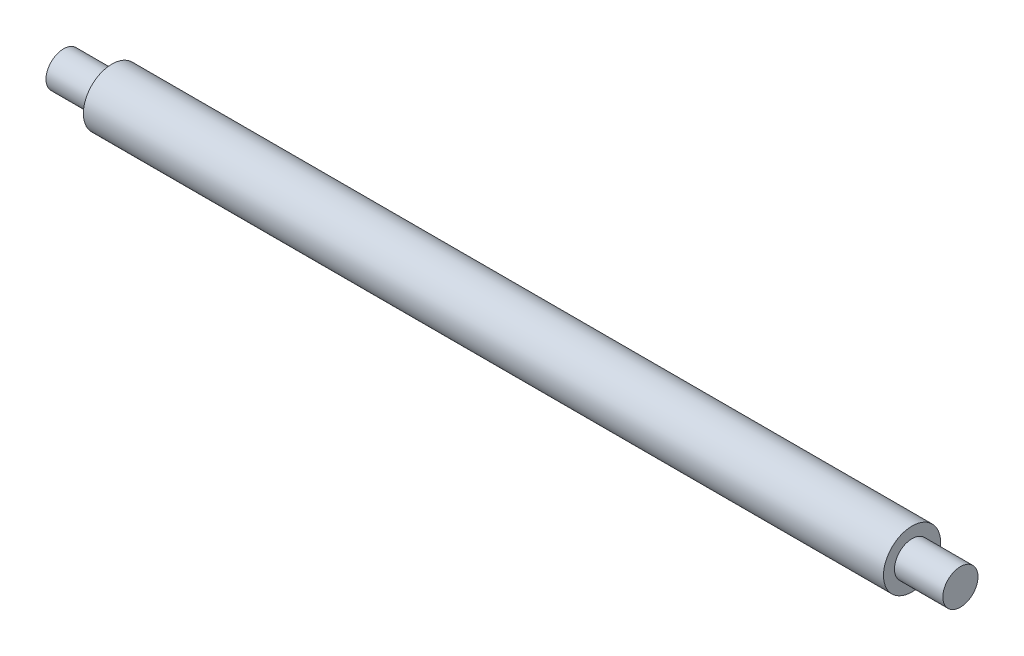
SolidWorks part; units mm, degrees
ref_plane "Front Plane" through (0, 0, 0) normal (0, 0, 1) x (1, 0, 0)
ref_plane "Top Plane" through (0, 0, 0) normal (0, 1, 0) x (1, 0, 0)
ref_plane "Right Plane" through (0, 0, 0) normal (1, 0, 0) x (0, 0, -1)
sketch "Sketch1" plane through (0, 0, 0) normal (0, 0, 1) x (1, 0, 0)
  line L0 (0, 0) -> (204, 0)
  line L1 (204, 0) -> (204, 4)
  line L2 (204, 4) -> (193, 4)
  line L3 (193, 4) -> (193, 6.5)
  line L4 (193, 6.5) -> (11, 6.5)
  line L5 (11, 6.5) -> (11, 4)
  line L6 (11, 4) -> (0, 4)
  line L7 (0, 4) -> (0, 0)
  dimension "D1" = 4
  dimension "D2" = 11
  dimension "D3" = 182
  dimension "D4" = 11
  dimension "D5" = 4
  dimension "D6" = 6.5
revolve "Revolve1" add sketch "Sketch1" angle 360 about L0
